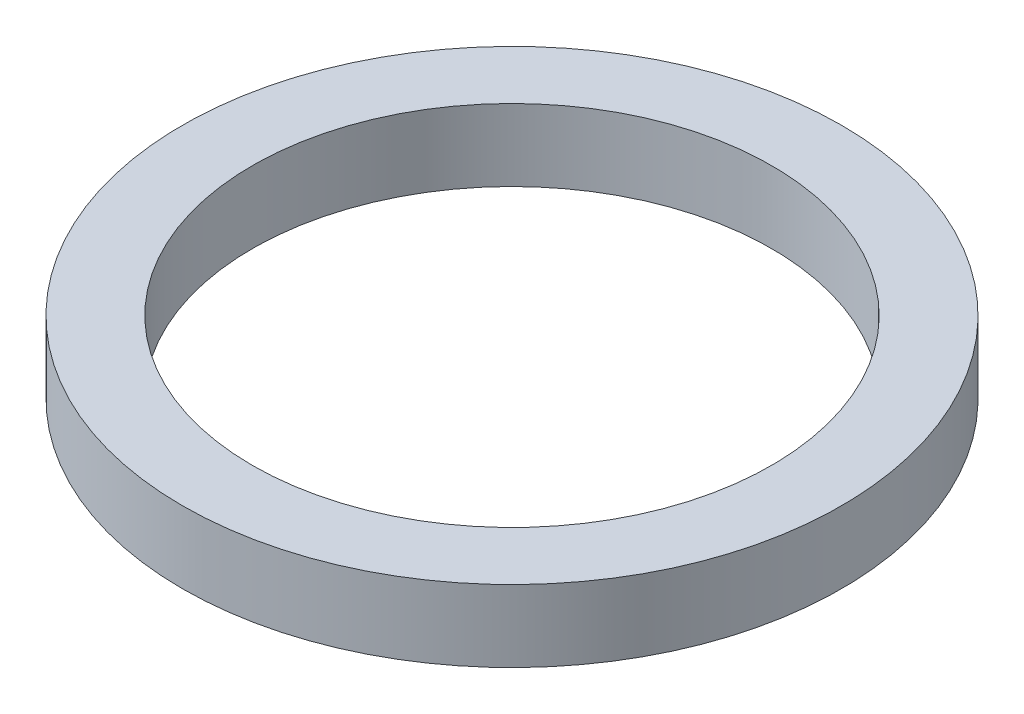
SolidWorks part; units mm, degrees
ref_plane "前视基准面" through (0, 0, 0) normal (0, 0, 1) x (1, 0, 0)
ref_plane "上视基准面" through (0, 0, 0) normal (0, 1, 0) x (1, 0, 0)
ref_plane "右视基准面" through (0, 0, 0) normal (1, 0, 0) x (0, 0, -1)
sketch "草图1" plane through (0, 0, 0) normal (0, 1, 0) x (1, 0, 0)
  circle A0 centre (0, 0) radius 82.5
  circle A1 centre (0, 0) radius 65
extrude "凸台-拉伸1" add sketch "草图1" along normal blind 18
